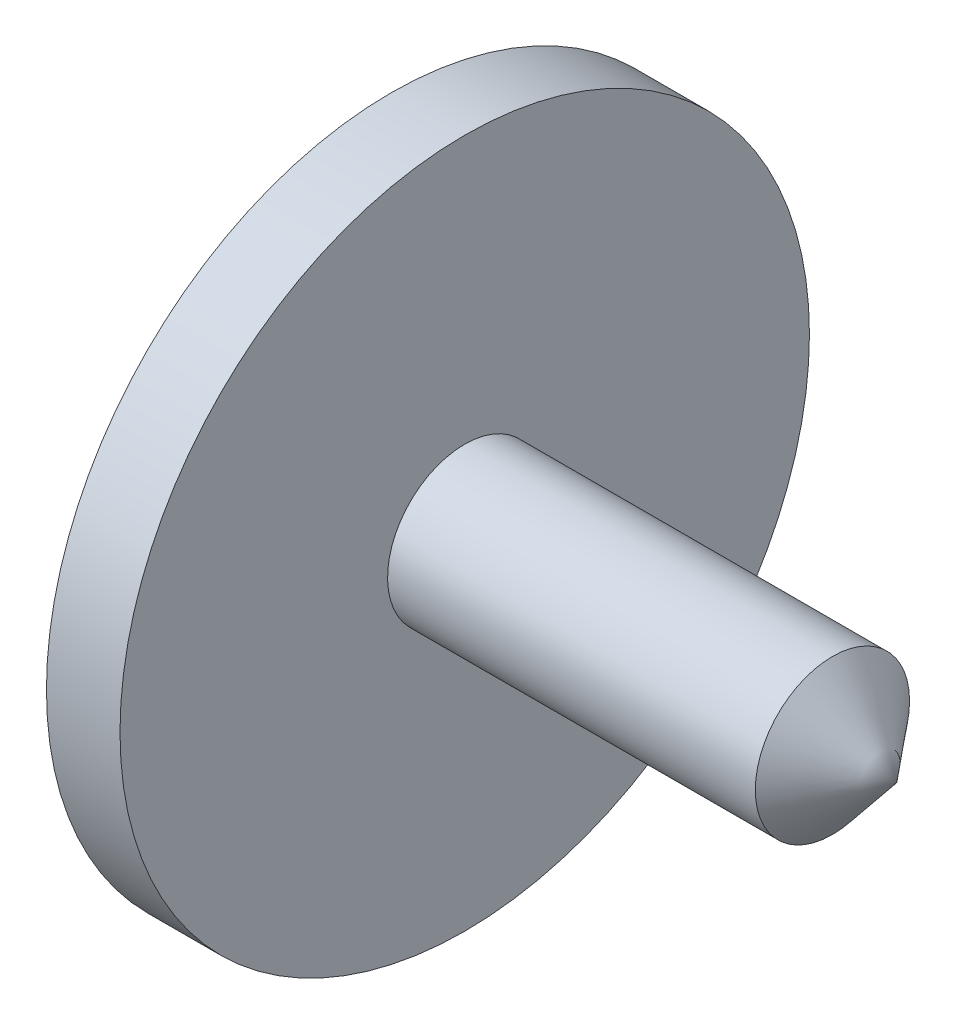
SolidWorks part; units mm, degrees
ref_plane "前视基准面" through (0, 0, 0) normal (0, 0, 1) x (1, 0, 0)
ref_plane "上视基准面" through (0, 0, 0) normal (0, 1, 0) x (1, 0, 0)
ref_plane "右视基准面" through (0, 0, 0) normal (1, 0, 0) x (0, 0, -1)
sketch "草图1" plane through (0, 0, 0) normal (0, 0, 1) x (1, 0, 0)
  line L0 (0, 0) -> (0, 37.5)
  line L1 (0, 37.5) -> (8, 37.5)
  line L2 (8, 37.5) -> (8, 8.3904)
  line L3 (8, 8.3904) -> (48, 8.3904)
  line L4 (48, 8.3904) -> (55, 0)
  line L5 (55, 0) -> (0, 0)
  dimension "D1" = 37.5
  dimension "D2" = 40
  dimension "D3" = 8
  dimension "D4" = 55
revolve "旋转1" add sketch "草图1" angle 360 about L5
